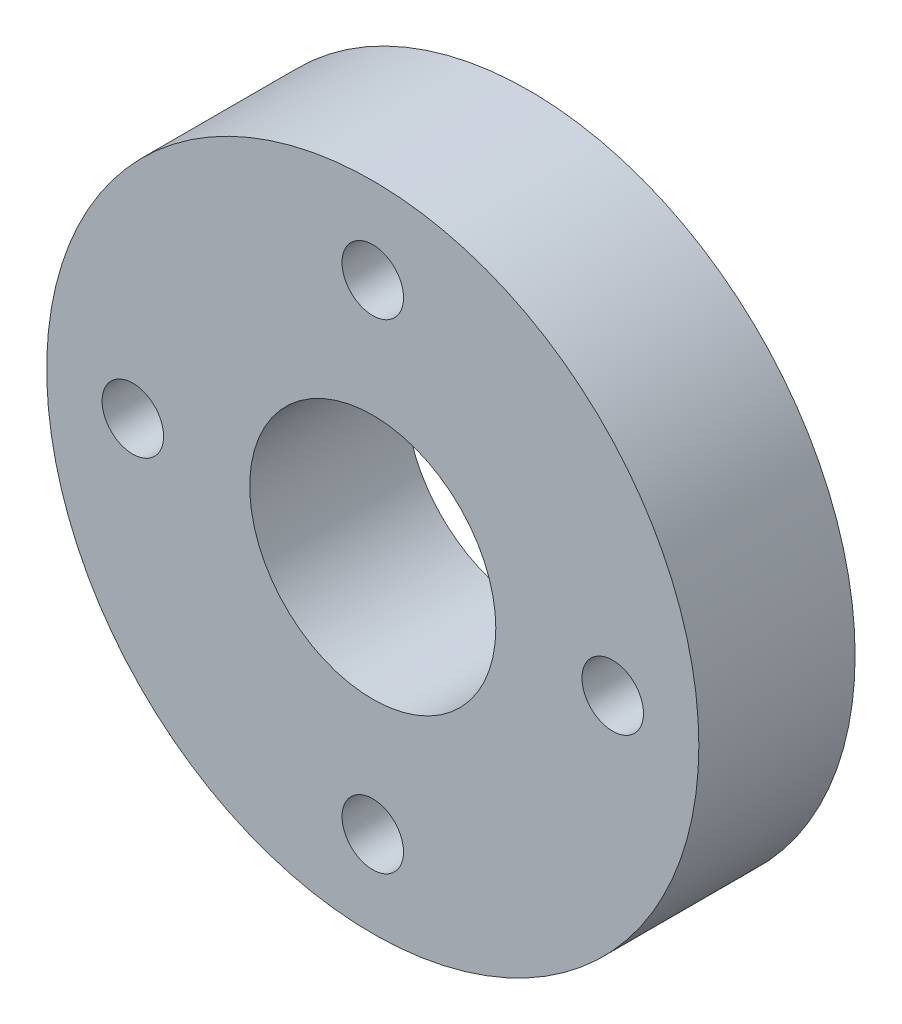
SolidWorks part; units mm, degrees
ref_plane "Front Plane" through (0, 0, 0) normal (0, 0, 1) x (1, 0, 0)
ref_plane "Top Plane" through (0, 0, 0) normal (0, 1, 0) x (1, 0, 0)
ref_plane "Right Plane" through (0, 0, 0) normal (1, 0, 0) x (0, 0, -1)
sketch "Sketch3" plane through (0, 0, 0) normal (0, 0, 1) x (1, 0, 0)
  circle A0 centre (0, 0) radius 13.25
  dimension "D1" = 26.5
extrude "Boss-Extrude1" add sketch "Sketch3" along normal blind 6.35
sketch "Sketch4" plane through (0, 0, 6.35) normal (0, 0, 1) x (1, 0, 0)
  circle A0 centre (0, 0) radius 5
  circle A1 centre (0, 0) radius 9.75 construction
  circle A2 centre (0, 9.75) radius 1.25
  circle A3 centre (9.75, 0) radius 1.25
  circle A4 centre (0, -9.75) radius 1.25
  circle A5 centre (-9.75, 0) radius 1.25
  point P15 (0, 0)
  dimension "D1" = 10
  dimension "D2" = 19.5
  dimension "D3" = 2.5
  dimension "D4" = 4
extrude "Cut-Extrude1" cut sketch "Sketch4" against normal blind 6.35
